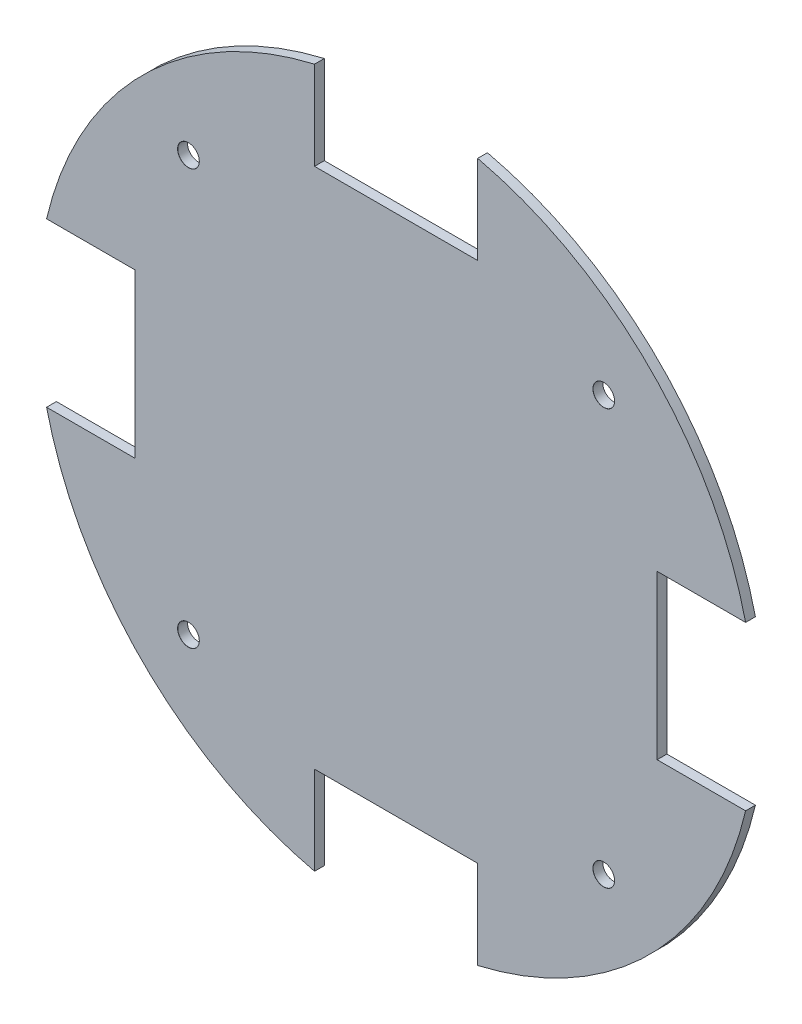
SolidWorks part; units mm, degrees
ref_plane "Plan de face" through (0, 0, 0) normal (0, 0, 1) x (1, 0, 0)
ref_plane "Plan de dessus" through (0, 0, 0) normal (0, 1, 0) x (1, 0, 0)
ref_plane "Plan de droite" through (0, 0, 0) normal (1, 0, 0) x (0, 0, -1)
sketch "Esquisse1" plane through (0, 0, 0) normal (0, 0, 1) x (1, 0, 0)
  line L0 (-110, 0) -> (216.2461, 0) construction
  line L1 (0, 0) -> (144.5817, 144.5817) construction
  line L2 (0, 0) -> (-110, -108.3105) construction
  line L3 (-50.4013, 97.7737) -> (-50.9377, 97.4954) construction
  line L4 (77.7817, -77.7817) -> (-91.5959, 91.5959) construction
  circle A0 centre (0, 0) radius 110
  dimension "D1" = 220
  dimension "D2" = 45
  dimension "D3" = 135
extrude "Boss.-Extru.1" add sketch "Esquisse1" along normal blind 3
sketch "Esquisse2" plane through (0, 0, 0) normal (0, 0, -1) x (-1, 0, 0)
  line L0 (0, 0) -> (-150.4659, 0) construction
  line L1 (80, 25) -> (110, 25)
  line L2 (80, 25) -> (80, -25)
  line L3 (80, -25) -> (110, -25)
  line L4 (110, 25) -> (110, -25)
  line L5 (0, 0) -> (246.8989, 0) construction
  line L6 (0, -138.736) -> (0, 127.688) construction
  line L8 (-110, 25) -> (-80, 25)
  line L9 (-110, 25) -> (-110, -25)
  line L10 (-110, -25) -> (-80, -25)
  line L11 (-80, 25) -> (-80, -25)
  line L12 (25, -110) -> (-25, -110)
  line L13 (25, -110) -> (25, -80)
  line L14 (25, -80) -> (-25, -80)
  line L15 (-25, -110) -> (-25, -80)
  line L16 (25, 110) -> (-25, 110)
  line L17 (25, 110) -> (25, 80)
  line L18 (25, 80) -> (-25, 80)
  line L19 (-25, 110) -> (-25, 80)
  point P11 (110, 0)
  point P24 (25, 95)
  point P25 (0, 110)
  dimension "D1" = 50
  dimension "D2" = 30
  dimension "D3" = 110
  dimension "D4" = 30
  dimension "D5" = 50
  dimension "D6" = 110
  dimension "D7" = 25
  dimension "D8" = 25
  dimension "D9" = 110
  dimension "D10" = 25
  dimension "D11" = 50
  dimension "D12" = 30
  dimension "D13" = 110
  dimension "D14" = 25
  dimension "D15" = 50
  dimension "D16" = 30
hole_wizard "Dégagement M61" positions "Esquisse3" profile "Esquisse4" hole size "M6" standard "ISO" end condition through all
sketch "Esquisse3" plane through (0, 0, 3) normal (0, 0, 1) x (1, 0, 0)
  line L0 (0, 0) -> (156.7015, 0) construction
  line L2 (-63.6396, -63.6396) -> (91.2817, 91.2817) construction
  line L4 (63.6396, -63.6396) -> (-88.7609, 88.7609) construction
  circle A0 centre (0, 0) radius 90
  point P0 (-63.6396, 63.6396)
  point P2 (63.6396, 63.6396)
  point P4 (-63.6396, -63.6396)
  point P6 (63.6396, -63.6396)
  dimension "D2" = 45
sketch "Esquisse4" plane through (-63.6396, 63.6396, 3) normal (1, 0, 0) x (0, -1, 0)
  line L0 (0, 0) -> (0, 3)
  line L1 (0, 3) -> (3.3, 3)
  line L2 (3.3, 3) -> (3.3, 0.025)
  line L3 (3.3, 0.025) -> (3.325, 0)
  line L5 (3.325, 0) -> (0, 0)
  line L6 (-3.3, 0.025) -> (-3.325, 0) construction
  line L11 (0, -6.35) -> (0, 107.95) construction
  dimension "Diamètre du perçage jusqu'au prochain" = 6.6
  dimension "Profondeur du perçage jusqu'au prochain" = 3
  dimension "Diamètre du fraisage entrant" = 6.65
  dimension "Angle du fraisage entrant" = 90
extrude "Enlèv. mat.-Extru.1" cut sketch "Esquisse2" against normal blind 10
